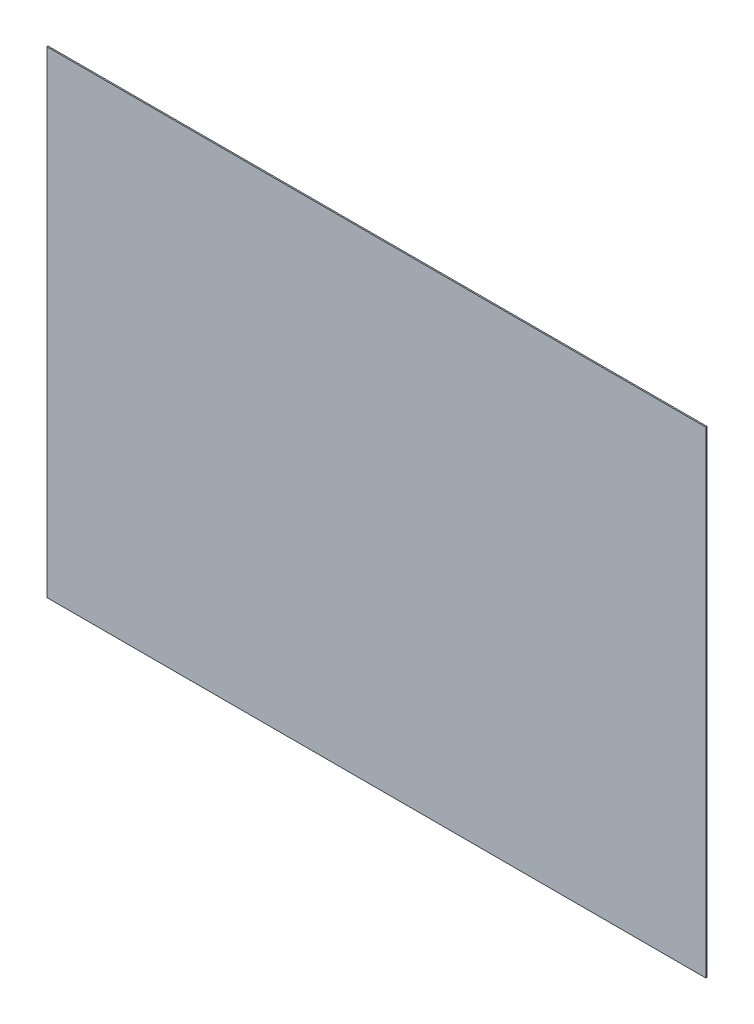
SolidWorks part; units mm, degrees
ref_plane "Alzado" through (0, 0, 0) normal (0, 0, 1) x (1, 0, 0)
ref_plane "Planta" through (0, 0, 0) normal (0, 1, 0) x (1, 0, 0)
ref_plane "Vista lateral" through (0, 0, 0) normal (1, 0, 0) x (0, 0, -1)
sketch "Croquis1" plane through (0, 0, 0) normal (0, 0, 1) x (1, 0, 0)
  line L1 (0, 0) -> (1519.3, 0)
  line L2 (0, 0) -> (0, -1100)
  line L3 (0, -1100) -> (1519.3, -1100)
  line L4 (1519.3, 0) -> (1519.3, -1100)
  dimension "D1" = 1519.3
  dimension "D2" = 1100
extrude "Saliente-Extruir1" add sketch "Croquis1" along normal blind 2.9
